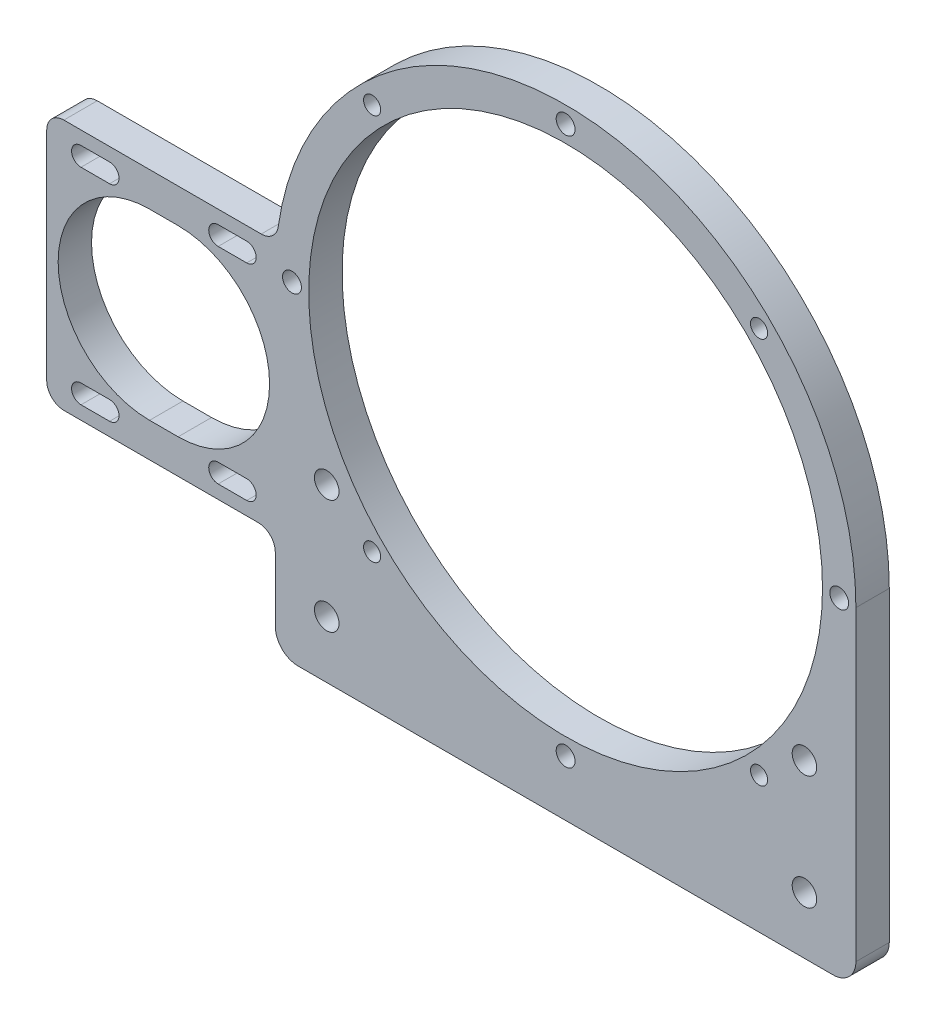
SolidWorks part; units mm, degrees
material "Acrylic (Medium-high impact)"
ref_plane "Front Plane" through (0, 0, 0) normal (0, 0, 1) x (1, 0, 0)
ref_plane "Top Plane" through (0, 0, 0) normal (0, 1, 0) x (1, 0, 0)
ref_plane "Right Plane" through (0, 0, 0) normal (1, 0, 0) x (0, 0, -1)
sketch "Sketch1" plane through (0, 0, 0) normal (0, 0, 1) x (1, 0, 0)
  line L0 (-50.8, 0) -> (-50.8, -57.658)
  line L1 (-50.8, 0) -> (-44.958, 0) construction
  line L2 (0, 0) -> (0, -57.658) construction
  line L3 (0, 0) -> (0, -62.9374) construction
  line L4 (50.8, 0) -> (50.8, -57.658)
  line L5 (-33.8556, 33.8556) -> (0, 0) construction
  line L8 (0, 0) -> (0, 47.879) construction
  line L12 (-50.8, -57.658) -> (0, -57.658)
  line L13 (-41.8, -57.658) -> (-41.8, -47.658) construction
  line L14 (-41.8, -47.658) -> (-41.8, -27.658) construction
  line L19 (0, -57.658) -> (50.8, -57.658)
  circle A1 centre (0, 0) radius 44.958
  arc A2 (-50.8, 0) -> (50.8, 0) centre (0, 0) cw
  circle A3 centre (-47.879, 0) radius 1.65
  circle A4 centre (0, 47.879) radius 1.65
  circle A6 centre (47.879, 0) radius 1.65
  circle A7 centre (0, -47.879) radius 1.65
  circle A10 centre (-41.8, -27.658) radius 2.15
  circle A11 centre (-33.8556, 33.8556) radius 1.5
  circle A12 centre (33.8556, 33.8556) radius 1.5
  circle A13 centre (33.8556, -33.8556) radius 1.5
  circle A14 centre (-33.8556, -33.8556) radius 1.5
  circle A15 centre (-41.8, -47.658) radius 2.15
  circle A16 centre (41.8, -47.658) radius 2.15
  circle A17 centre (41.8, -27.658) radius 2.15
  point P29 (0, 0)
  point P46 (0, 0)
  dimension "D2" = 89.916
  dimension "D5" = 3.3
  dimension "D6" = 4
  dimension "D7" = 45
  dimension "D10" = 62.9374
  dimension "D14" = 3
  dimension "D17" = 4.3
  dimension "D3" = 57.658
  dimension "D4" = 101.6
  dimension "D18" = 20
  dimension "D19" = 10
  dimension "D20" = 9
  dimension "D15" = 4
extrude "Boss-Extrude1" add sketch "Sketch1" along normal blind 5.842
fillet "Fillet1" radius 4 2 edges at (50.8, -57.658, 2.921) (-50.8, -57.658, 2.921)
sketch "Sketch2" plane through (0, 0, 5.842) normal (0, 0, 1) x (1, 0, 0)
  line L0 (-50.5923, 4.5885) -> (-90.8, 4.5885)
  line L1 (-79.8, 0.5885) -> (-67.8, -17.4115) construction
  line L2 (-90.8, 4.5885) -> (-90.8, -39.4115)
  line L3 (-90.8, -39.4115) -> (-50.8, -39.4115)
  line L4 (-90.8, -17.4115) -> (-67.8, -17.4115) construction
  line L5 (-50.5923, 4.5885) -> (-50.8, -39.4115)
  line L6 (-67.8, -17.4115) -> (-72.8, -17.4115) construction
  line L7 (-67.8, -33.4115) -> (-72.8, -33.4115)
  line L8 (-79.8, 0.5885) -> (-79.8, -35.4115) construction
  line L9 (-79.8, -35.4115) -> (-55.8, -35.4115) construction
  line L10 (-55.8, -35.4115) -> (-55.8, 0.5885) construction
  line L11 (-55.8, 0.5885) -> (-79.8, 0.5885) construction
  line L12 (-67.8, -17.4115) -> (-79.8, -35.4115) construction
  line L13 (-55.8, 0.5885) -> (-67.8, -17.4115) construction
  line L14 (-67.8, -17.4115) -> (-55.8, -35.4115) construction
  line L16 (-67.8, -17.4115) -> (0, 0) construction
  line L17 (-67.8, -1.4115) -> (-72.8, -1.4115)
  line L18 (-50.8, 0) -> (-50.8, -53.658) construction
  line L19 (-55.8, 0.5885) -> (-60.8, 0.5885) construction
  line L20 (-55.8, -1.0615) -> (-60.8, -1.0615)
  line L21 (-55.8, 2.2385) -> (-60.8, 2.2385)
  line L22 (-79.8, 0.5885) -> (-84.8, 0.5885) construction
  line L23 (-79.8, -1.0615) -> (-84.8, -1.0615)
  line L24 (-79.8, 2.2385) -> (-84.8, 2.2385)
  line L25 (-55.8, -35.4115) -> (-60.8, -35.4115) construction
  line L26 (-55.8, -37.0615) -> (-60.8, -37.0615)
  line L27 (-55.8, -33.7615) -> (-60.8, -33.7615)
  line L28 (-79.8, -35.4115) -> (-84.8, -35.4115) construction
  line L29 (-79.8, -37.0615) -> (-84.8, -37.0615)
  line L30 (-79.8, -33.7615) -> (-84.8, -33.7615)
  arc A0 (-67.8, -33.4115) -> (-67.8, -1.4115) centre (-67.8, -17.4115) ccw
  arc A1 (-55.8, -1.0615) -> (-55.8, 2.2385) centre (-55.8, 0.5885) ccw
  arc A2 (-60.8, 2.2385) -> (-60.8, -1.0615) centre (-60.8, 0.5885) ccw
  arc A3 (-79.8, -1.0615) -> (-79.8, 2.2385) centre (-79.8, 0.5885) ccw
  arc A4 (-84.8, 2.2385) -> (-84.8, -1.0615) centre (-84.8, 0.5885) ccw
  arc A5 (-72.8, -1.4115) -> (-72.8, -33.4115) centre (-72.8, -17.4115) ccw
  arc A6 (50.8, 0) -> (-50.8, 0) centre (0, 0) ccw construction
  arc A7 (-55.8, -37.0615) -> (-55.8, -33.7615) centre (-55.8, -35.4115) ccw
  arc A8 (-60.8, -33.7615) -> (-60.8, -37.0615) centre (-60.8, -35.4115) ccw
  arc A9 (-79.8, -37.0615) -> (-79.8, -33.7615) centre (-79.8, -35.4115) ccw
  arc A10 (-84.8, -33.7615) -> (-84.8, -37.0615) centre (-84.8, -35.4115) ccw
  point P1 (-70.3, -17.4115)
  point P9 (-58.3, 0.5885)
  point P26 (-82.3, 0.5885)
  point P36 (-58.3, -35.4115)
  point P43 (-82.3, -35.4115)
  dimension "D4" = 17
  dimension "D5" = 24
  dimension "D6" = 5
  dimension "D2" = 16
  dimension "D11" = 1.65
  dimension "D1" = 6
  dimension "D3" = 70
  dimension "D7" = 4
  dimension "D8" = 5
  dimension "D10" = 36
extrude "Boss-Extrude2" add sketch "Sketch2" against normal through all contours L0
fillet "Fillet2" radius 3 4 edges at (-50.8, -39.4115, 2.921) (-90.8, -39.4115, 2.921) (-90.8, 4.5885, 2.921) (-50.5923, 4.5885, 2.921)
